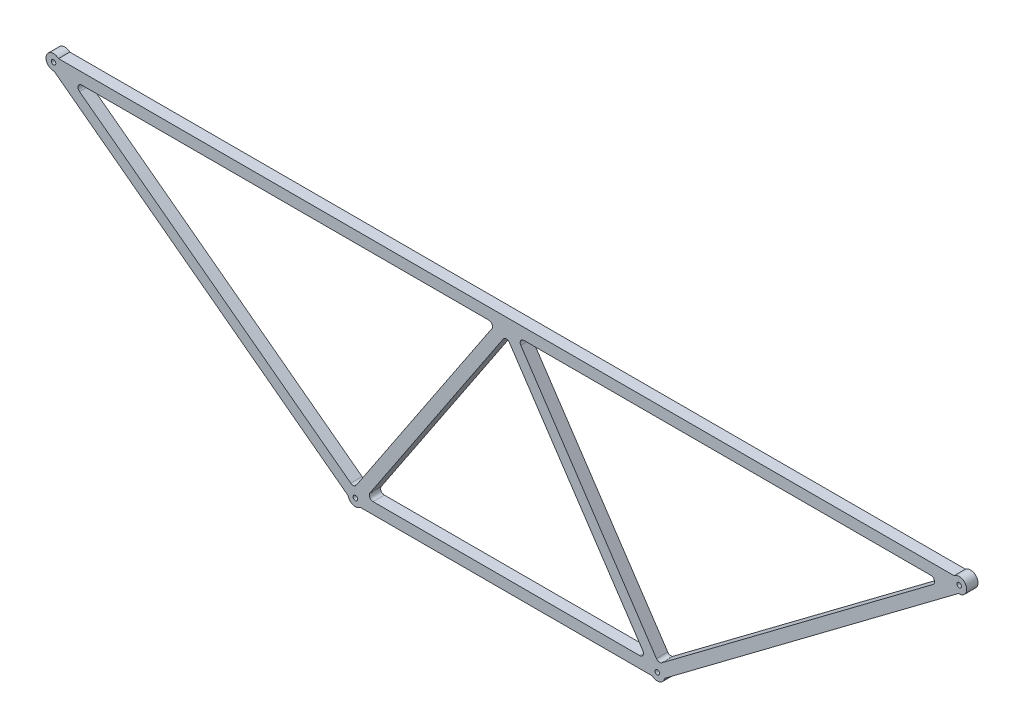
SolidWorks part; units mm, degrees
material "AISI 1020"
ref_plane "Front Plane" through (0, 0, 0) normal (0, 0, 1) x (1, 0, 0)
ref_plane "Top Plane" through (0, 0, 0) normal (0, 1, 0) x (1, 0, 0)
ref_plane "Right Plane" through (0, 0, 0) normal (1, 0, 0) x (0, 0, -1)
sketch "Sketch1" plane through (0, 0, 0) normal (0, 0, 1) x (1, 0, 0)
  line L0 (0, 0) -> (-600, 0) construction
  line L1 (-600, 0) -> (-200, -300) construction
  line L2 (-200, -300) -> (0, 0) construction
  line L3 (0, 0) -> (200, -300) construction
  line L4 (200, -300) -> (600, 0) construction
  line L5 (600, 0) -> (0, 0) construction
  line L6 (-200, -300) -> (200, -300) construction
  circle A0 centre (-600, 0) radius 3
  circle A1 centre (-200, -300) radius 3
  circle A2 centre (200, -300) radius 3
  circle A3 centre (600, 0) radius 3
  circle A4 centre (-600, 0) radius 10
  circle A5 centre (-200, -300) radius 10
  circle A6 centre (200, -300) radius 10
  circle A7 centre (600, 0) radius 10
  point P14 (0, 0)
  dimension "D7" = 6
  dimension "D8" = 20
  dimension "D1" = 500
  dimension "D2" = 400
  dimension "D3" = 400
  dimension "D4" = 200
  dimension "D5" = 360.5551
  dimension "D6" = 56.31
extrude "Boss-Extrude1" add sketch "Sketch1" along normal mid plane 15
sketch "Sketch2" plane through (0, 0, 0) normal (0, 0, 1) x (1, 0, 0)
  line L4 (201.8426, -289.2431) -> (577.5, -7.5)
  line L5 (200, -307.5) -> (202.5, -307.5)
  line L6 (204.5, -306) -> (622.5, 7.5)
  line L7 (622.5, 7.5) -> (-622.5, 7.5)
  line L8 (-622.5, 7.5) -> (-204.5, -306)
  line L9 (-200, -307.5) -> (200, -307.5)
  line L10 (204.5, -306) -> (202.5, -307.5)
  line L11 (577.5, -7.5) -> (14.0139, -7.5)
  line L12 (-577.5, -7.5) -> (-201.8426, -289.2431)
  line L13 (-185.9861, -292.5) -> (185.9861, -292.5)
  line L14 (-185.9861, -292.5) -> (0, -13.5208)
  line L15 (0, -13.5208) -> (185.9861, -292.5)
  line L16 (-200, -307.5) -> (-202.5, -307.5)
  line L17 (-204.5, -306) -> (-202.5, -307.5)
  line L18 (14.0139, -7.5) -> (201.8426, -289.2431)
  line L20 (-14.0139, -7.5) -> (-577.5, -7.5)
  line L30 (-201.8426, -289.2431) -> (-14.0139, -7.5)
extrude "Boss-Extrude2" add sketch "Sketch2" along normal mid plane 15
sketch "Sketch3" plane through (0, 0, 0) normal (0, 0, 1) x (1, 0, 0)
  line L0 (605.7724, 8.1657) -> (623.6767, 10.8991)
  line L1 (623.6767, 10.8991) -> (625.2864, -4.2155)
  line L2 (625.2864, -4.2155) -> (609.4688, -3.216)
  line L3 (0, -8.25) -> (0, 8.25) construction
  line L4 (-625.2864, -4.2155) -> (-609.4688, -3.216)
  line L5 (-623.6767, 10.8991) -> (-625.2864, -4.2155)
  line L6 (-605.7724, 8.1657) -> (-623.6767, 10.8991)
  circle A0 centre (-600, 0) radius 3
  circle A1 centre (-200, -300) radius 3
  circle A2 centre (200, -300) radius 3
  circle A3 centre (600, 0) radius 3
  arc A4 (605.7724, 8.1657) -> (609.4688, -3.216) centre (600, 0) cw
  circle A5 centre (600, 0) radius 10 construction
  arc A6 (-605.7724, 8.1657) -> (-609.4688, -3.216) centre (-600, 0) ccw
extrude "Cut-Extrude1" cut sketch "Sketch3" against normal mid plane 30
fillet "Fillet1" radius 5 9 edges at (-201.8426, -289.2431, 0) (-577.5, -7.5, 0) (577.5, -7.5, 0) (14.0139, -7.5, 0) (-14.0139, -7.5, 0) (0, -13.5208, 0) (185.9861, -292.5, 0) (201.8426, -289.2431, 0) (-185.9861, -292.5, 0)
